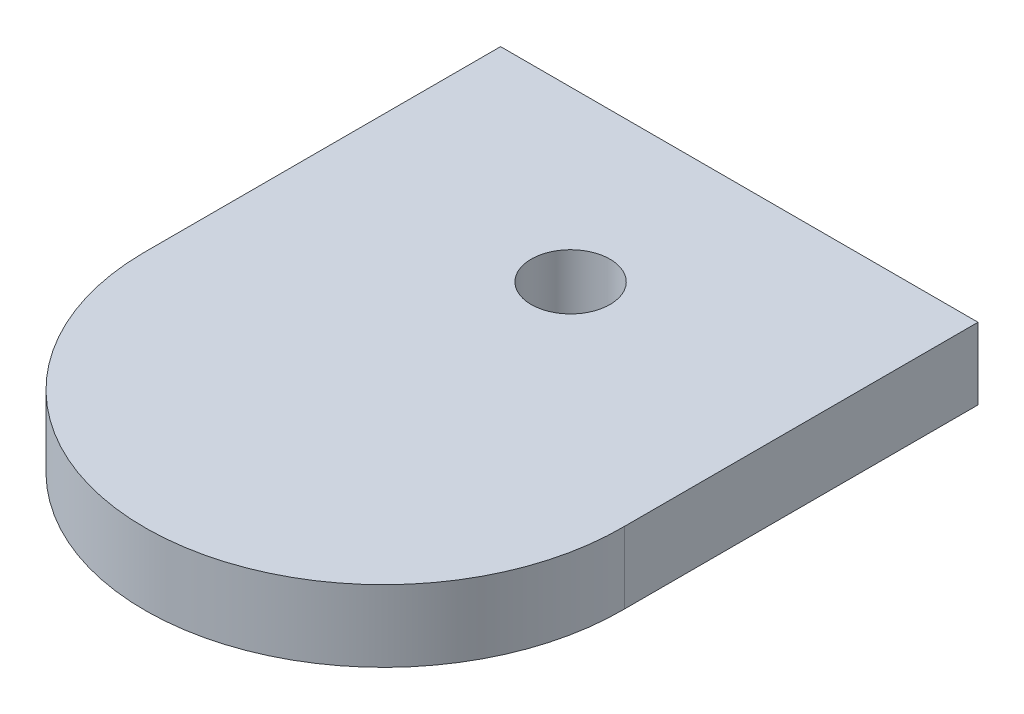
SolidWorks part; units mm, degrees
ref_plane "前视基准面" through (0, 0, 0) normal (0, 0, 1) x (1, 0, 0)
ref_plane "上视基准面" through (0, 0, 0) normal (0, 1, 0) x (1, 0, 0)
ref_plane "右视基准面" through (0, 0, 0) normal (1, 0, 0) x (0, 0, -1)
other "Configuration Table"
sketch "草图1" plane through (0, 0, 0) normal (0, 1, 0) x (1, 0, 0)
  line L0 (10, 0.0988) -> (10, 14.9012)
  line L1 (10, 14.9012) -> (-10, 14.9012)
  line L2 (-10, 14.9012) -> (-10, -0.0988)
  arc A0 (10, 0.0988) -> (-10, -0.0988) centre (0, 0) cw
  circle A1 centre (0, 7.8339) radius 1.65
  dimension "D1" = 10
  dimension "D2" = 15
extrude "凸台-拉伸1" add sketch "草图1" along normal blind 3
